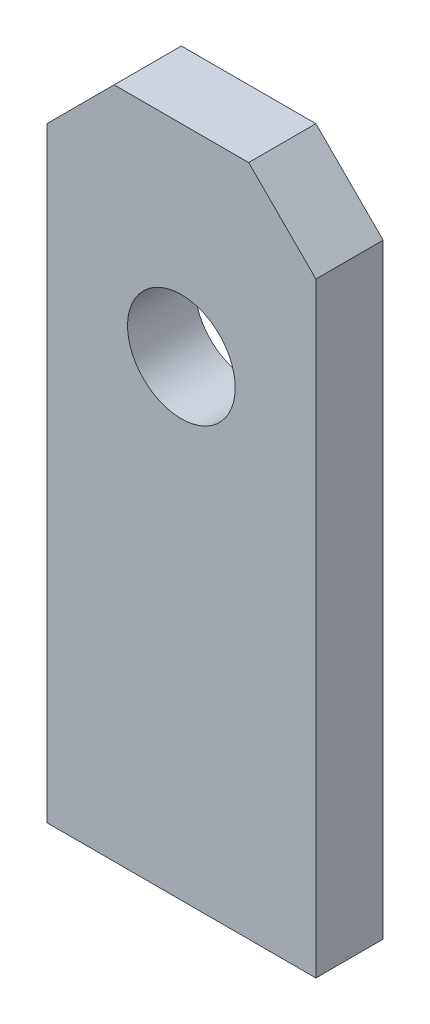
SolidWorks part; units mm, degrees
material "ASTM A36 Steel"
ref_plane "Front Plane" through (0, 0, 0) normal (0, 0, 1) x (1, 0, 0)
ref_plane "Top Plane" through (0, 0, 0) normal (0, 1, 0) x (1, 0, 0)
ref_plane "Right Plane" through (0, 0, 0) normal (1, 0, 0) x (0, 0, -1)
sketch "Sketch1" plane through (0, 0, 0) normal (0, 0, 1) x (1, 0, 0)
  line L0 (-20, -50) -> (20, -50)
  line L1 (20, -50) -> (20, 40)
  line L2 (20, 40) -> (10, 50)
  line L3 (10, 50) -> (-10, 50)
  line L4 (-10, 50) -> (-20, 40)
  line L5 (-20, 40) -> (-20, -50)
  circle A0 centre (0, 20) radius 8
  point P2 (0, 50)
  point P10 (0, 0)
  dimension "D8" = 70
  dimension "D9" = 16
  dimension "D1" = 40
  dimension "D2" = 100
  dimension "D3" = 20
  dimension "D4" = 45
  dimension "D5" = 45
  dimension "D6" = 10
  dimension "D7" = 50
extrude "Boss-Extrude1" add sketch "Sketch1" along normal mid plane 10
